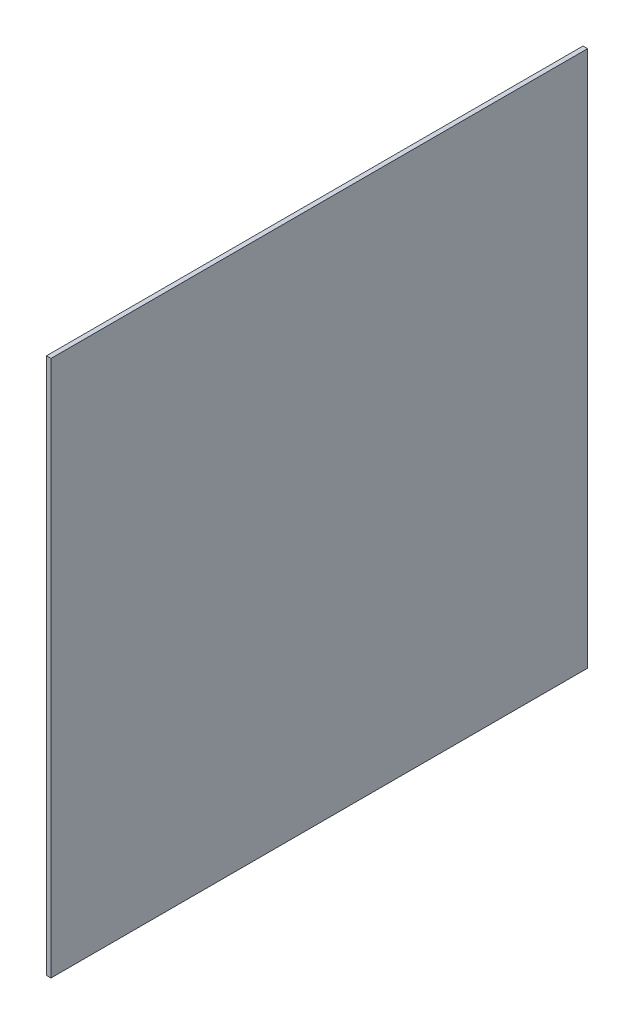
SolidWorks part; units mm, degrees
material "3003 Alloy"
ref_plane "Front Plane" through (0, 0, 0) normal (0, 0, 1) x (1, 0, 0)
ref_plane "Top Plane" through (0, 0, 0) normal (0, 1, 0) x (1, 0, 0)
ref_plane "Right Plane" through (0, 0, 0) normal (1, 0, 0) x (0, 0, -1)
sketch "Sketch1" plane through (0, 0, 0) normal (1, 0, 0) x (0, 0, -1)
  line L1 (117.3, -117.3) -> (-117.3, -117.3)
  line L2 (117.3, -117.3) -> (117.3, 117.3)
  line L3 (117.3, 117.3) -> (-117.3, 117.3)
  line L4 (-117.3, -117.3) -> (-117.3, 117.3)
  line L5 (117.3, -117.3) -> (-117.3, 117.3) construction
  line L6 (117.3, 117.3) -> (-117.3, -117.3) construction
  point P0 (0, 0)
  dimension "D1" = 234.6
  dimension "D2" = 234.6
extrude "Boss-Extrude1" add sketch "Sketch1" along normal blind 2
